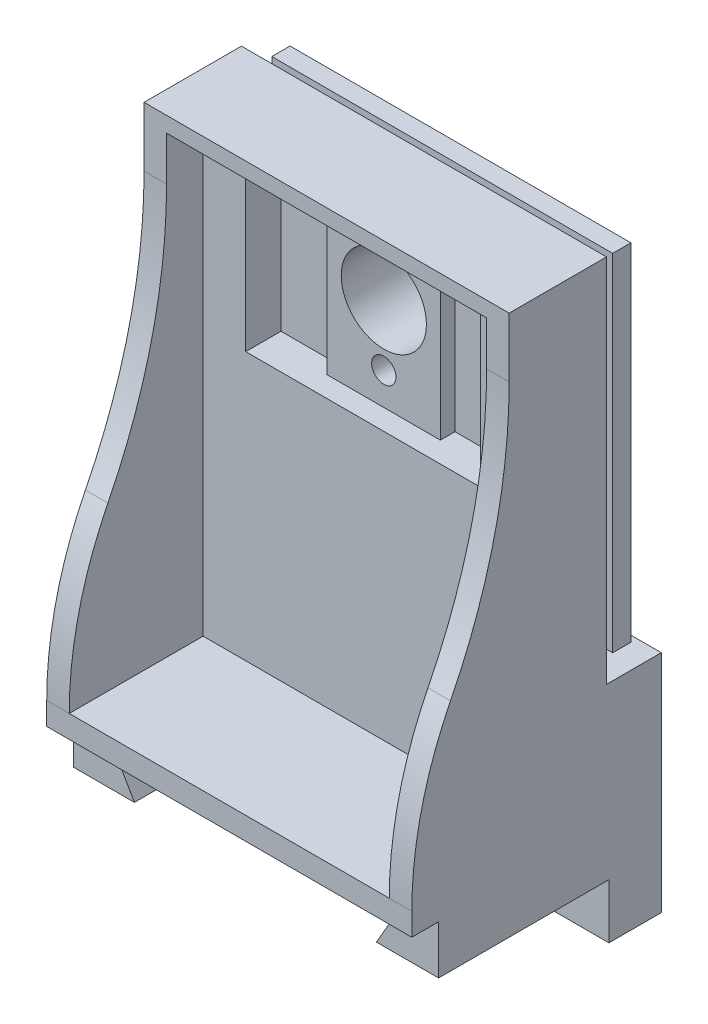
SolidWorks part; units mm, degrees
ref_plane "Front Plane" through (0, 0, 0) normal (0, 0, 1) x (1, 0, 0)
ref_plane "Top Plane" through (0, 0, 0) normal (0, 1, 0) x (1, 0, 0)
ref_plane "Right Plane" through (0, 0, 0) normal (1, 0, 0) x (0, 0, -1)
sketch "laserslip_pcb" plane through (0, 0, 0) normal (0, 0, 1) x (1, 0, 0)
  line L0 (0, 2) -> (2, 2) construction
  line L1 (0, 0) -> (26, 0) construction
  line L2 (0, 0) -> (0, 37) construction
  line L3 (0, 37) -> (26, 37) construction
  line L4 (26, 0) -> (26, 37) construction
  line L5 (2, 2) -> (2, 0) construction
  line L6 (26, 2) -> (24, 2) construction
  line L7 (24, 2) -> (24, 0) construction
  line L8 (2, 37) -> (2, 35) construction
  line L9 (2, 35) -> (0, 35) construction
  line L10 (24, 37) -> (24, 35) construction
  line L11 (24, 35) -> (26, 35) construction
  circle A0 centre (2, 35) radius 1.05 construction
  circle A1 centre (24, 35) radius 1.05 construction
  circle A2 centre (24, 2) radius 1.05 construction
  circle A3 centre (2, 2) radius 1.05 construction
  circle A4 centre (13, 31.463) radius 2.964 construction
  point P23 (13, 37)
  point P24 (0, 0)
  dimension "D3" = 2.1
  dimension "D6" = 5.928
  dimension "D1" = 37
  dimension "D2" = 26
  dimension "D4" = 2
  dimension "D5" = 31.463
sketch "mic_pcb_vert" plane through (0, 0, 0) normal (0, 0, 1) x (1, 0, 0)
  line L0 (5.58, 26.2675) -> (20.58, 26.2675) construction
  line L1 (5.58, 26.2675) -> (5.58, 7.2675) construction
  line L2 (5.58, 7.2675) -> (20.58, 7.2675) construction
  line L3 (20.58, 26.2675) -> (20.58, 7.2675) construction
  line L4 (8.08, 16.7675) -> (5.58, 16.7675) construction
  line L5 (18.08, 16.7675) -> (20.58, 16.7675) construction
  line L6 (18.08, 16.7675) -> (13.08, 16.7675) construction
  line L7 (13.08, 16.7675) -> (13.08, 26.2675) construction
  circle A0 centre (8.08, 16.7675) radius 1.05 construction
  circle A1 centre (18.08, 16.7675) radius 1.05 construction
  point P11 (5.58, 16.7675)
  point P12 (20.58, 16.7675)
  point P15 (5.476, 21.931)
  point P16 (39.0657, 18.5)
  point P17 (5.58, 7.2675)
  dimension "D3" = 2.1
  dimension "D1" = 19
  dimension "D2" = 15
  dimension "D4" = 2.5
sketch "mic_pcb_hor" plane through (0, 0, 0) normal (0, 0, 1) x (1, 0, 0)
  line L0 (3.5, 37) -> (22.5, 37) construction
  line L1 (3.5, 37) -> (3.5, 22) construction
  line L2 (3.5, 22) -> (22.5, 22) construction
  line L3 (22.5, 37) -> (22.5, 22) construction
  line L4 (13, 29.5) -> (22.5, 29.5) construction
  line L5 (13, 24.5) -> (13, 22) construction
  line L6 (13, 33.45) -> (13, 34.5) construction
  line L7 (13, 29.5) -> (13, 33.45) construction
  line L8 (13, 34.5) -> (13, 37) construction
  line L9 (0, 37) -> (26, 37) construction
  circle A0 centre (13, 24.5) radius 1.05 construction
  circle A1 centre (13, 34.5) radius 1.05 construction
  circle A2 centre (5.84, 24.42) radius 1 construction
  circle A3 centre (5.84, 26.96) radius 1 construction
  circle A4 centre (5.84, 29.5) radius 1 construction
  circle A5 centre (5.84, 32.04) radius 1 construction
  circle A6 centre (5.84, 34.58) radius 1 construction
  circle A7 centre (20.16, 24.42) radius 1 construction
  circle A8 centre (20.16, 26.96) radius 1 construction
  circle A9 centre (20.16, 29.5) radius 1 construction
  circle A10 centre (20.16, 32.04) radius 1 construction
  circle A11 centre (20.16, 34.58) radius 1 construction
  point P4 (5.7831, 25.0633)
  point P11 (0, 0)
  point P29 (0, 0)
  point P39 (0, 0)
  point P40 (0, 0)
  dimension "D3" = 2.1
  dimension "D8" = 2
  dimension "D1" = 15
  dimension "D2" = 19
  dimension "D4" = 2.5
  dimension "D5" = 1.963
  dimension "D7" = 2.34
  dimension "D9" = 2.54
  dimension "D6" = 5
sketch "Sketch2" plane through (0, 0, 0) normal (0, 0, 1) x (1, 0, 0)
  line L0 (0, 0) -> (-2, 0) construction
  line L1 (-2, 8) -> (28, 8)
  line L2 (-2, 8) -> (-2, -10.5)
  line L3 (-2, -10.5) -> (28, -10.5)
  line L4 (28, 8) -> (28, -10.5)
  line L5 (26, 0) -> (28, 0) construction
  line L6 (0, 0) -> (26, 0) construction
  dimension "D1" = 2
  dimension "D2" = 8
  dimension "D3" = 10.5
extrude "Boss-Extrude1" add sketch "Sketch2" along normal blind 4.5
sketch "Sketch3" plane through (0, 0, 4.5) normal (0, 0, 1) x (1, 0, 0)
  line L0 (0, 0) -> (26, 0) construction
  line L1 (-2, 38.4159) -> (28, 38.4159)
  line L2 (-2, 38.4159) -> (-2, -6)
  line L4 (28, 38.4159) -> (28, -6)
  line L6 (28, -10.5) -> (28, 8) construction
  line L7 (-2, 8) -> (-2, -10.5) construction
  line L8 (-2, -6) -> (3.0094, -6)
  line L9 (3.0094, -6) -> (0.7, -2)
  line L10 (0.7, -2) -> (25.2, -2)
  line L11 (25.2, -2) -> (22.8906, -6)
  line L12 (22.8906, -6) -> (28, -6)
  dimension "D1" = 60
  dimension "D2" = 60
  dimension "D3" = 2.7
  dimension "D4" = 4
  dimension "D5" = 2.8
  dimension "D6" = 2
extrude "Boss-Extrude2" add sketch "Sketch3" along normal blind 5
sketch "Sketch4" plane through (0, 0, 9.5) normal (0, 0, 1) x (1, 0, 0)
  line L0 (0, 18.5) -> (-0.15, 18.5) construction
  line L1 (-0.15, 37.15) -> (26.15, 37.15)
  line L2 (-0.15, 37.15) -> (-0.15, -0.15)
  line L3 (-0.15, -0.15) -> (26.15, -0.15)
  line L4 (26.15, 37.15) -> (26.15, -0.15)
  line L5 (0, 0) -> (0, 37) construction
  line L6 (13, 37) -> (13, 37.15) construction
  line L7 (0, 37) -> (26, 37) construction
  line L8 (-2, 38.4159) -> (-2, -6)
  line L9 (-2, -6) -> (3.0094, -6)
  line L10 (3.0094, -6) -> (0.7, -2)
  line L11 (0.7, -2) -> (25.2, -2)
  line L12 (25.2, -2) -> (22.8906, -6)
  line L13 (22.8906, -6) -> (28, -6)
  line L14 (28, -6) -> (28, 38.4159)
  line L15 (28, 38.4159) -> (-2, 38.4159)
  line L16 (-2, 38.4159) -> (-2, -6)
  line L17 (-2, -6) -> (3.0094, -6)
  line L18 (3.0094, -6) -> (0.7, -2)
  line L19 (0.7, -2) -> (25.2, -2)
  line L20 (25.2, -2) -> (22.8906, -6)
  line L21 (22.8906, -6) -> (28, -6)
  line L22 (28, -6) -> (28, 38.4159)
  line L23 (28, 38.4159) -> (-2, 38.4159)
  dimension "D2" = 0.15
  dimension "D1" = 0
extrude "Boss-Extrude3" add sketch "Sketch4" along normal blind 9
sketch "Sketch5" plane through (0, 0, 18.5) normal (0, 0, 1) x (1, 0, 0)
  line L0 (28, -6) -> (28, 38.4159) construction
  line L1 (-2, 38.4159) -> (28, 38.4159)
  line L2 (-2, 38.4159) -> (-2, -2)
  line L3 (-2, -2) -> (28, -2)
  line L4 (28, 38.4159) -> (28, -2)
  line L5 (0.7, -2) -> (25.2, -2) construction
  line L6 (26.15, -0.15) -> (-0.15, -0.15)
  line L7 (26.15, -0.15) -> (26.15, 37.15)
  line L8 (26.15, 37.15) -> (-0.15, 37.15)
  line L9 (-0.15, -0.15) -> (-0.15, 37.15)
extrude "Boss-Extrude4" add sketch "Sketch5" along normal blind 2
sketch "Sketch6" plane through (28, 0, 0) normal (1, 0, 0) x (0, 0, -1)
  line L0 (-20.5, -2) -> (-20.5, 38.4159) construction
  line L1 (-12.5, 38.4159) -> (-29.9203, 38.4159)
  line L2 (-12.5, 33.5206) -> (-12.5, 38.4159)
  line L3 (-20.5, 38.4159) -> (-4.5, 38.4159) construction
  line L4 (-9.5, -0.15) -> (-9.5, 37.15) construction
  line L8 (-20.5, -0.15) -> (-29.9203, -0.15)
  line L9 (-29.9203, -0.15) -> (-29.9203, 38.4159)
  arc A0 (-17.3201, 13.2337) -> (-20.5, -0.15) centre (9.2549, -0.15) ccw
  arc A2 (-17.3201, 13.2337) -> (-12.5, 33.5206) centre (-57.6021, 33.5206) ccw
  dimension "D1" = 3
extrude "Cut-Extrude1" cut sketch "Sketch6" against normal through all
sketch "Sketch7" plane through (0, 0, 0) normal (0, 0, -1) x (-1, 0, 0)
  line L0 (2, -10.5) -> (-28, -10.5) construction
  line L1 (-13, -9) -> (-13, 49991) construction
  circle A0 centre (-19.5, -6.25) radius 2.75
  circle A1 centre (-6.5, -6.25) radius 2.75
  point P4 (-13, -10.5)
  dimension "D2" = 5.5
  dimension "D1" = 4.25
  dimension "D3" = 6.5
extrude "Cut-Extrude2" cut sketch "Sketch7" against normal blind 3
sketch "Sketch8" plane through (0, 0, 3) normal (0, 0, -1) x (-1, 0, 0)
  circle A0 centre (-19.5, -6.25) radius 1.65
  circle A1 centre (-19.5, -6.25) radius 2.75 construction
  circle A2 centre (-19.5, -6.25) radius 2.75 construction
  circle A3 centre (-6.5, -6.25) radius 2.75 construction
  circle A4 centre (-6.5, -6.25) radius 2.75 construction
  circle A5 centre (-6.5, -6.25) radius 1.65
  dimension "D1" = 3.3
extrude "Cut-Extrude3" cut sketch "Sketch8" against normal through all
sketch "Sketch9" plane through (-2, 0, 0) normal (-1, 0, 0) x (0, 0, 1)
  line L0 (18.5, -6) -> (4.5, -6) construction
  line L1 (18.3, -6) -> (18.5, -6)
  line L2 (18.3, -6) -> (18.3, -2)
  line L3 (18.3, -2) -> (18.5, -2)
  line L4 (18.5, -6) -> (18.5, -2)
  dimension "D1" = 0.2
extrude "tolerance_cut1" cut sketch "Sketch9" against normal through all
sketch "Sketch10" plane through (0, 0, 4.5) normal (0, 0, 1) x (1, 0, 0)
  line L8 (28, -6) -> (22.8906, -6)
  line L9 (22.8906, -6) -> (25.2, -2)
  line L10 (25.2, -2) -> (0.7, -2)
  line L11 (0.7, -2) -> (3.0094, -6)
  line L12 (3.0094, -6) -> (-2, -6)
  line L13 (-2, -6) -> (-2, -10.5)
  line L14 (-2, -10.5) -> (28, -10.5)
  line L15 (28, -10.5) -> (28, -6)
  line L16 (28, -6) -> (22.8906, -6)
  line L17 (22.8906, -6) -> (25.2, -2)
  line L18 (25.2, -2) -> (0.7, -2)
  line L19 (0.7, -2) -> (3.0094, -6)
  line L20 (3.0094, -6) -> (-2, -6)
  line L21 (-2, -6) -> (-2, -10.5)
  line L22 (-2, -10.5) -> (28, -10.5)
  line L23 (28, -10.5) -> (28, -6)
  dimension "D1" = 0
extrude "tolerance_cut2" cut sketch "Sketch10" against normal blind 0.2
sketch "Sketch12" plane through (0, 0, 4.5) normal (0, 0, -1) x (-1, 0, 0)
  line L0 (2, 38.4159) -> (2, 8) construction
  line L1 (-26.0111, 36.427) -> (0.0111, 36.427)
  line L2 (-26.0111, 36.427) -> (-26.0111, 9.9889)
  line L3 (-26.0111, 9.9889) -> (0.0111, 9.9889)
  line L4 (0.0111, 36.427) -> (0.0111, 9.9889)
  line L5 (-28, 38.4159) -> (2, 38.4159) construction
  line L6 (-13, 38.4159) -> (-13, 36.427) construction
  line L7 (-26.0111, 23.208) -> (-28, 23.208) construction
  line L8 (-28, 8) -> (-28, 38.4159) construction
  line L9 (-13, 34.427) -> (-13, 36.427) construction
  circle A0 centre (-13, 31.463) radius 2.964 construction
  point P6 (2, 23.208)
  point P7 (0.0111, 23.208)
  point P10 (-13, 38.4159)
  point P11 (-13, 36.427)
  dimension "D1" = 2
extrude "Boss-Extrude6" add sketch "Sketch12" along normal blind 1.5
sketch "Sketch13" plane through (0, 0, 3) normal (0, 0, -1) x (-1, 0, 0)
  line L0 (0.0111, 36.427) -> (-26.0111, 36.427) construction
  line L1 (-27.0055, 37.4215) -> (1.0055, 37.4215)
  line L2 (-27.0055, 37.4215) -> (-27.0055, 8.9945)
  line L3 (-27.0055, 8.9945) -> (1.0055, 8.9945)
  line L4 (1.0055, 37.4215) -> (1.0055, 8.9945)
  line L5 (-26.0111, 36.427) -> (-26.0111, 9.9889) construction
  line L6 (-27.0055, 23.208) -> (-26.0111, 23.208) construction
  line L7 (-26.0111, 36.427) -> (-26.0111, 9.9889) construction
  line L8 (-13, 36.427) -> (-13, 37.4215) construction
  line L9 (-27.0055, 23.208) -> (-28, 23.208) construction
  line L10 (-28, 8) -> (-28, 38.4159) construction
  point P6 (-13, 36.427)
  point P7 (-13, 37.4215)
  point P10 (-26.0111, 23.208)
  point P11 (-27.0055, 23.208)
  dimension "D1" = 0.9945
extrude "Boss-Extrude7" add sketch "Sketch13" along normal blind 1.5
sketch "Sketch16" plane through (0, 0, 1.5) normal (0, 0, -1) x (-1, 0, 0)
  line L0 (0.0111, 36.427) -> (-26.0111, 36.427) construction
  line L1 (-26.0111, 36.427) -> (-26.0111, 9.9889) construction
  line L2 (0.0111, 36.427) -> (-26.0111, 36.427) construction
  line L3 (-26.0111, 36.427) -> (-26.0111, 9.9889) construction
  line L4 (-26.0111, 9.9889) -> (0.0111, 9.9889) construction
  line L5 (0.0111, 9.9889) -> (0.0111, 36.427) construction
  line L6 (-26.0111, 9.9889) -> (0.0111, 9.9889) construction
  line L7 (0.0111, 9.9889) -> (0.0111, 36.427) construction
  line L8 (-24.5111, 26.1694) -> (-24.5111, 24.6694)
  line L9 (-26.0111, 32.1694) -> (-24.5111, 32.1694)
  line L10 (-26.0111, 32.1694) -> (-26.0111, 30.6694)
  line L11 (-26.0111, 30.6694) -> (-24.5111, 30.6694)
  line L12 (-24.5111, 32.1694) -> (-24.5111, 30.6694)
  line L13 (-26.0111, 26.1694) -> (-26.0111, 24.6694)
  line L14 (-26.0111, 26.1694) -> (-24.5111, 26.1694)
  line L15 (-26.0111, 24.6694) -> (-24.5111, 24.6694)
  line L16 (-24.5111, 20.1694) -> (-24.5111, 18.6694)
  line L17 (-26.0111, 20.1694) -> (-26.0111, 18.6694)
  line L18 (-26.0111, 20.1694) -> (-24.5111, 20.1694)
  line L19 (-26.0111, 18.6694) -> (-24.5111, 18.6694)
  line L20 (-24.5111, 14.1694) -> (-24.5111, 12.6694)
  line L21 (-26.0111, 14.1694) -> (-26.0111, 12.6694)
  line L22 (-26.0111, 14.1694) -> (-24.5111, 14.1694)
  line L23 (-26.0111, 12.6694) -> (-24.5111, 12.6694)
  line L24 (-13, 8.9945) -> (-13, 37.6069) construction
  line L25 (-21.7649, 9.9889) -> (-20.2649, 9.9889)
  line L26 (-21.7649, 9.9889) -> (-21.7649, 11.4889)
  line L27 (-21.7649, 11.4889) -> (-20.2649, 11.4889)
  line L28 (-20.2649, 9.9889) -> (-20.2649, 11.4889)
  line L29 (-20.2649, 36.427) -> (-18.7649, 36.427)
  line L30 (-20.2649, 36.427) -> (-20.2649, 34.927)
  line L31 (-20.2649, 34.927) -> (-18.7649, 34.927)
  line L32 (-18.7649, 36.427) -> (-18.7649, 34.927)
  line L33 (-27.0055, 8.9945) -> (1.0055, 8.9945) construction
  line L34 (-4.2351, 11.4889) -> (-5.7351, 11.4889)
  line L35 (-5.7351, 9.9889) -> (-5.7351, 11.4889)
  line L36 (-4.2351, 9.9889) -> (-5.7351, 9.9889)
  line L37 (-4.2351, 9.9889) -> (-4.2351, 11.4889)
  line L38 (0.0111, 14.1694) -> (-1.4889, 14.1694)
  line L39 (0.0111, 14.1694) -> (0.0111, 12.6694)
  line L40 (0.0111, 12.6694) -> (-1.4889, 12.6694)
  line L41 (-1.4889, 14.1694) -> (-1.4889, 12.6694)
  line L42 (0.0111, 20.1694) -> (-1.4889, 20.1694)
  line L43 (0.0111, 20.1694) -> (0.0111, 18.6694)
  line L44 (0.0111, 18.6694) -> (-1.4889, 18.6694)
  line L45 (-1.4889, 20.1694) -> (-1.4889, 18.6694)
  line L46 (0.0111, 26.1694) -> (-1.4889, 26.1694)
  line L47 (0.0111, 26.1694) -> (0.0111, 24.6694)
  line L48 (0.0111, 24.6694) -> (-1.4889, 24.6694)
  line L49 (-1.4889, 26.1694) -> (-1.4889, 24.6694)
  line L50 (0.0111, 30.6694) -> (-1.4889, 30.6694)
  line L51 (-1.4889, 32.1694) -> (-1.4889, 30.6694)
  line L52 (0.0111, 32.1694) -> (-1.4889, 32.1694)
  line L53 (0.0111, 32.1694) -> (0.0111, 30.6694)
  line L54 (-5.7351, 34.927) -> (-7.2351, 34.927)
  line L55 (-7.2351, 36.427) -> (-7.2351, 34.927)
  line L56 (-5.7351, 36.427) -> (-7.2351, 36.427)
  line L57 (-5.7351, 36.427) -> (-5.7351, 34.927)
  dimension "D1" = 1.5
  dimension "D2" = 4
extrude "silicone_channels" cut sketch "Sketch16" against normal blind 3
sketch "Sketch19" plane through (0, 0, 9.5) normal (0, 0, 1) x (1, 0, 0)
  line L0 (-0.15, 37.15) -> (26.15, 37.15) construction
  line L1 (3.35, 37.15) -> (22.65, 37.15)
  line L2 (3.35, 37.15) -> (3.35, 21.85)
  line L3 (3.35, 21.85) -> (22.65, 21.85)
  line L4 (22.65, 37.15) -> (22.65, 21.85)
  line L5 (3.5, 29.5) -> (3.35, 29.5) construction
  line L6 (3.5, 37) -> (3.5, 22) construction
  line L7 (13, 37) -> (13, 37.15) construction
  line L8 (3.5, 37) -> (22.5, 37) construction
  point P6 (13, 21.85)
  point P8 (3.35, 29.5)
extrude "pcb_cavity" cut sketch "Sketch19" against normal blind 1.7
sketch "Sketch15" plane through (0, 0, 7.8) normal (0, 0, 1) x (1, 0, 0)
  circle A0 centre (13, 34.5) radius 1
  circle A1 centre (13, 24.5) radius 1
  point P6 (13, 34.5)
  point P7 (13, 24.5)
  dimension "D1" = 2
extrude "pcb_mount_holes" cut sketch "Sketch15" against normal blind 5
sketch "Sketch20" plane through (0, 0, 7.8) normal (0, 0, 1) x (1, 0, 0)
  line L0 (3.35, 21.85) -> (22.65, 21.85) construction
  line L1 (3.35, 37.15) -> (8.35, 37.15)
  line L2 (3.35, 37.15) -> (3.35, 21.85)
  line L3 (3.35, 21.85) -> (8.35, 21.85)
  line L4 (8.35, 37.15) -> (8.35, 21.85)
  line L5 (-0.15, 37.15) -> (26.15, 37.15) construction
  line L6 (22.65, 21.85) -> (17.65, 21.85)
  line L7 (22.65, 21.85) -> (22.65, 37.15)
  line L8 (22.65, 37.15) -> (17.65, 37.15)
  line L9 (17.65, 21.85) -> (17.65, 37.15)
  dimension "D1" = 5
extrude "solder_cavity" cut sketch "Sketch20" against normal blind 1.2
sketch "Sketch21" plane through (0, 0, 7.8) normal (0, 0, 1) x (1, 0, 0)
  circle A0 centre (13, 29.5) radius 0.5
  dimension "D1" = 1
extrude "audio_channel" cut sketch "Sketch21" against normal through all
sketch "Sketch22" plane through (0, 0, 1.5) normal (0, 0, -1) x (-1, 0, 0)
  circle A0 centre (-13, 29.5) radius 3.5
  dimension "D1" = 7
extrude "Cut-Extrude13" cut sketch "Sketch22" against normal through all
